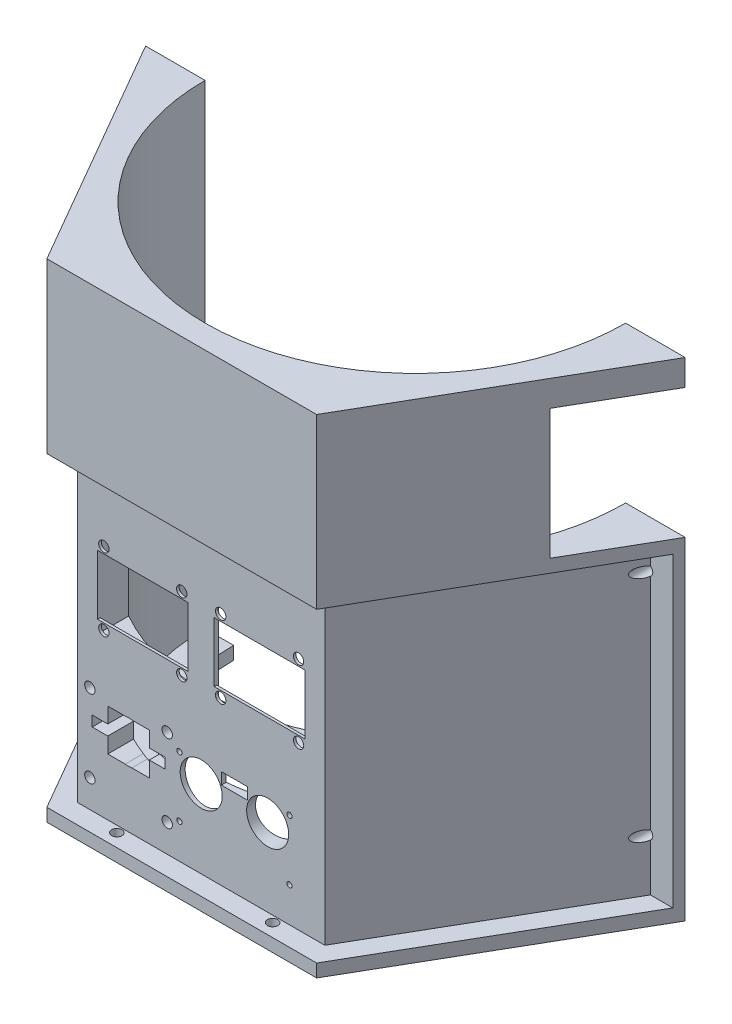
SolidWorks part; units mm, degrees
ref_plane "Front Plane" through (0, 0, 0) normal (0, 0, 1) x (1, 0, 0)
ref_plane "Top Plane" through (0, 0, 0) normal (0, 1, 0) x (1, 0, 0)
ref_plane "Right Plane" through (0, 0, 0) normal (1, 0, 0) x (0, 0, -1)
sketch "Sketch1" plane through (0, 0, 0) normal (0, 1, 0) x (1, 0, 0)
  line L0 (-103.923, 0) -> (103.923, 0)
  line L4 (-103.923, 0) -> (-51.9615, -90)
  line L5 (-51.9615, -90) -> (51.9615, -90)
  line L6 (51.9615, -90) -> (103.923, 0)
  line L8 (77.9423, 45) -> (51.9615, 90) [skipped]
  line L9 (51.9615, 90) -> (-51.9615, 90) [skipped]
  line L10 (-77.9423, 45) -> (-103.923, 0) [skipped]
  arc A0 (-70, 0) -> (70, 0) centre (0, 0) ccw
  arc A2 (-90, 0) -> (90, 0) centre (0, 0) ccw construction
  dimension "D1" = 140
  dimension "D2" = 90
extrude "Boss-Extrude2" add sketch "Sketch1" along normal blind 5 contours A0 L0 L4 L5 L6
sketch "Sketch3" plane through (0, 5, 0) normal (0, 1, 0) x (1, 0, 0)
  line L0 (-103.923, 0) -> (-81, 0)
  line L4 (-93.5307, -3) -> (-47.6314, -82.5)
  line L5 (-47.6314, -82.5) -> (47.6314, -82.5)
  line L6 (47.6314, -82.5) -> (93.5307, -3)
  line L7 (81, 0) -> (103.923, 0)
  line L8 (47.6314, 82.5) -> (-47.6314, 82.5) [skipped]
  line L9 (95.2628, 0) -> (71.4471, 41.25) [skipped]
  line L10 (-71.4471, 41.25) -> (-95.2628, 0) [skipped]
  line L11 (102.191, -3) -> (93.5307, -3)
  line L12 (103.923, 0) -> (102.191, -3)
  line L13 (51.9615, -90) -> (103.923, 0) construction
  line L14 (-102.191, -3) -> (-93.5307, -3)
  line L15 (-103.923, 0) -> (-102.191, -3)
  line L16 (-103.923, 0) -> (-51.9615, -90) construction
  arc A0 (-81, 0) -> (81, 0) centre (0, 0) ccw
  arc A1 (-82.5, 0) -> (82.5, 0) centre (0, 0) ccw construction
  dimension "D1" = 162
extrude "Boss-Extrude3" add sketch "Sketch3" along normal blind 118
sketch "Sketch4" plane through (0, 123, 0) normal (0, 1, 0) x (1, 0, 0)
  line L0 (-103.923, 0) -> (-81, 0)
  line L4 (-103.923, 0) -> (-51.9615, -90)
  line L5 (-51.9615, -90) -> (51.9615, -90)
  line L6 (51.9615, -90) -> (103.923, 0)
  line L7 (81, 0) -> (103.923, 0)
  line L8 (51.9615, 90) -> (-51.9615, 90) [skipped]
  line L9 (103.923, 0) -> (77.9423, 45) [skipped]
  line L10 (-77.9423, 45) -> (-103.923, 0) [skipped]
  arc A0 (-81, 0) -> (81, 0) centre (0, 0) ccw
  arc A1 (-90, 0) -> (90, 0) centre (0, 0) ccw construction
  dimension "D1" = 162
  dimension "D2" = 180
extrude "Boss-Extrude4" add sketch "Sketch4" along normal blind 5
sketch "Sketch5" plane through (0, 128, 0) normal (0, 1, 0) x (1, 0, 0)
  line L0 (84.8705, -33) -> (51.9615, -90)
  line L1 (51.9615, -90) -> (-51.9615, -90)
  line L2 (-51.9615, -90) -> (-103.923, 0)
  line L3 (-103.923, 0) -> (-81, 0)
  line L5 (84.8705, -33) -> (73.973, -33)
  arc A0 (-81, 0) -> (73.973, -33) centre (0, 0) ccw
extrude "Boss-Extrude5" add sketch "Sketch5" along normal blind 50
sketch "Sketch6" plane through (0, 178, 0) normal (0, 1, 0) x (1, 0, 0)
  line L0 (-103.923, 0) -> (-51.9615, -90)
  line L1 (-51.9615, -90) -> (51.9615, -90)
  line L2 (51.9615, -90) -> (103.923, 0)
  line L3 (84.8705, -33) -> (103.923, 0) construction
  line L4 (103.923, 0) -> (81, 0)
  line L5 (-81, 0) -> (-103.923, 0)
  arc A0 (-81, 0) -> (81, 0) centre (0, 0) ccw
extrude "Boss-Extrude6" add sketch "Sketch6" along normal blind 10
sketch "Sketch7" plane through (0, 0, 82.5) normal (0, 0, 1) x (1, 0, 0)
  line L0 (0, 123) -> (0, 93)
  line L1 (-47.6314, 123) -> (47.6314, 123) construction
  line L2 (0, 93) -> (5, 93)
  line L3 (0, 93) -> (-5, 93)
  line L4 (5, 93) -> (40, 93)
  line L5 (40, 93) -> (40, 70)
  line L6 (40, 70) -> (5, 70)
  line L7 (-5, 93) -> (-40, 93)
  line L8 (-40, 93) -> (-40, 70)
  line L9 (-40, 70) -> (-5, 70)
  line L10 (-5, 93) -> (-5, 70)
  line L11 (5, 93) -> (5, 70)
  dimension "D1" = 30
  dimension "D2" = 5
  dimension "D3" = 5
  dimension "D4" = 35
  dimension "D5" = 23
  dimension "D6" = 35
  dimension "D7" = 35
  dimension "D8" = 35
  dimension "D9" = 23
extrude "Cut-Extrude1" cut sketch "Sketch7" against normal blind 1 contours L10 L7 L8 L9 | L4 L11 L6 L5
sketch "Sketch8" plane through (0, 0, 81.5) normal (0, 0, 1) x (1, 0, 0)
  line L0 (-40, 93) -> (-40, 98)
  line L1 (-40, 70) -> (-40, 65)
  line L2 (-40, 98) -> (-5, 98)
  line L3 (-5, 98) -> (-5, 65)
  line L4 (-5, 65) -> (-40, 65)
  line L5 (-40, 70) -> (-40, 93)
  line L6 (5, 93) -> (40, 93) construction
  line L7 (5, 70) -> (5, 98)
  line L8 (5, 98) -> (40.0427, 98)
  line L9 (40.0427, 98) -> (40.0427, 65)
  line L10 (40.0427, 65) -> (5, 65)
  line L11 (5, 65) -> (5, 70)
  dimension "D1" = 5
  dimension "D2" = 5
  dimension "D3" = 5
extrude "Cut-Extrude2" cut sketch "Sketch8" against normal blind 50
sketch "Sketch9" plane through (0, 0, 82.5) normal (0, 0, 1) x (1, 0, 0)
  line L0 (-47.6314, 5) -> (47.6314, 5) construction
  circle A0 centre (0, 35) radius 8.1
  circle A1 centre (25.6, 35) radius 8.1
  circle A2 centre (-28, 35) radius 8.1
  dimension "D2" = 16.2
  dimension "D3" = 25.6
  dimension "D4" = 16.2
  dimension "D5" = 16.2
  dimension "D6" = 28
  dimension "D1" = 30
extrude "Cut-Extrude3" cut sketch "Sketch9" against normal blind 10
sketch "Sketch10" plane through (0, 0, 0) normal (0, 0, -1) x (-1, 0, 0)
  line L0 (-92.4615, 128) -> (-92.4615, 113)
  line L1 (-103.923, 128) -> (-81, 128) construction
  line L2 (-92.4615, 25) -> (-92.4615, 0)
  line L3 (-70, 0) -> (-103.923, 0) construction
  line L4 (92.4615, 188) -> (92.4615, 113)
  line L5 (81, 188) -> (103.923, 188) construction
  line L7 (92.4615, 25) -> (92.4615, 0)
  line L8 (103.923, 0) -> (70, 0) construction
  circle A0 centre (92.4615, 113) radius 2
  circle A1 centre (-92.4615, 113) radius 2
  circle A2 centre (-92.4615, 25) radius 2
  circle A3 centre (92.4615, 25) radius 2
  dimension "D5" = 4
  dimension "D6" = 4
  dimension "D7" = 4
  dimension "D8" = 4
  dimension "D1" = 15
  dimension "D2" = 25
  dimension "D3" = 25
  dimension "D4" = 75
extrude "Cut-Extrude4" cut sketch "Sketch10" against normal blind 10
sketch "Sketch11" plane through (0, 0, 0) normal (0, -1, 0) x (1, 0, 0)
  line L0 (0, 90) -> (0, 85)
  line L1 (-51.9615, 90) -> (51.9615, 90) construction
  line L2 (0, 85) -> (30, 85)
  line L3 (0, 85) -> (-30, 85)
  circle A0 centre (-30, 85) radius 2
  circle A1 centre (30, 85) radius 2
  dimension "D4" = 4
  dimension "D5" = 4
  dimension "D1" = 5
  dimension "D2" = 30
  dimension "D3" = 30
extrude "Cut-Extrude5" cut sketch "Sketch11" against normal blind 10
sketch "Sketch12" plane through (0, 0, 82.5) normal (0, 0, 1) x (1, 0, 0)
  line L0 (-40, 93) -> (-40, 95.5)
  line L1 (-40, 95.5) -> (-37.5, 95.5)
  line L2 (-5, 93) -> (-5, 95.5)
  line L3 (-5, 95.5) -> (-7.5, 95.5)
  line L4 (-40, 70) -> (-40, 67.5)
  line L5 (-40, 67.5) -> (-37.5, 67.5)
  line L6 (-5, 70) -> (-5, 67.5)
  line L7 (-5, 67.5) -> (-7.5, 67.5)
  line L8 (0, 0) -> (0, 88.9926) construction
  circle A0 centre (-37.5, 95.5) radius 2
  circle A1 centre (-7.5, 95.5) radius 2
  circle A2 centre (-7.5, 67.5) radius 2
  circle A3 centre (-37.5, 67.5) radius 2
  circle A4 centre (7.5, 67.5) radius 2
  circle A5 centre (37.5, 67.5) radius 2
  circle A6 centre (7.5, 95.5) radius 2
  circle A7 centre (37.5, 95.5) radius 2
  dimension "D9" = 4
  dimension "D10" = 4
  dimension "D11" = 4
  dimension "D12" = 4
  dimension "D1" = 2.5
  dimension "D2" = 2.5
  dimension "D3" = 2.5
  dimension "D4" = 2.5
  dimension "D5" = 2.5
  dimension "D6" = 2.5
  dimension "D7" = 2.5
  dimension "D8" = 2.5
extrude "Cut-Extrude6" cut sketch "Sketch12" against normal blind 10
sketch "Sketch13" plane through (0, 0, 82.5) normal (0, 0, 1) x (1, 0, 0)
  line L1 (12.8, 38.5) -> (17.85, 38.5)
  line L2 (12.8, 43) -> (35.4, 43)
  line L3 (35.4, 43) -> (35.4, 17)
  line L4 (35.4, 17) -> (-9.8, 17)
  line L5 (-9.8, 17) -> (-9.8, 43)
  line L6 (-9.8, 43) -> (12.8, 43)
  line L7 (12.8, 38.5) -> (7.75, 38.5)
  line L8 (7.75, 38.5) -> (7.75, 43)
  line L9 (17.85, 38.5) -> (17.85, 43)
  circle A0 centre (34, 41.6) radius 1
  circle A1 centre (-8.4, 41.6) radius 1
  circle A2 centre (-8.4, 18.4) radius 1
  circle A3 centre (34, 18.4) radius 1
  point P0 (-8.4, 43)
  point P1 (-9.8, 41.6)
  point P4 (34, 43)
  point P9 (35.4, 41.6)
  dimension "D9" = 2
  dimension "D10" = 2
  dimension "D11" = 2
  dimension "D12" = 2
  dimension "D13" = 1.4
  dimension "D14" = 1.4
  dimension "D15" = 1.4
  dimension "D16" = 1.4
  dimension "D1" = 26
  dimension "D2" = 1.4
  dimension "D3" = 45.2
  dimension "D4" = 22.6
  dimension "D5" = 26
  dimension "D6" = 1.4
  dimension "D7" = 1.4
  dimension "D8" = 1.4
  dimension "D17" = 4.5
  dimension "D18" = 5.05
  dimension "D19" = 5.05
extrude "Cut-Extrude7" cut sketch "Sketch13" against normal blind 10 contours A1 | L1 L9 L2 L6 L8 L7 | A2 | A3 | A0
sketch "Sketch14" plane through (0, 0, 82.5) normal (0, 0, 1) x (1, 0, 0)
  line L0 (-28, 35) -> (-28, 48)
  line L1 (-28, 48) -> (-10.5, 48)
  line L2 (-10.5, 48) -> (-10.5, 8)
  line L3 (-10.5, 8) -> (-45.5, 8)
  line L4 (-45.5, 8) -> (-45.5, 48)
  line L5 (-45.5, 48) -> (-28, 48)
  circle A0 centre (-13.1, 45.7) radius 2
  circle A1 centre (-42.9, 45.7) radius 2
  circle A2 centre (-42.9, 15.7) radius 2
  circle A3 centre (-13.1, 15.7) radius 2
  circle M14 centre (-8.4, 41.6) radius 1
  dimension "D6" = 2.3
  dimension "D7" = 2.6
  dimension "D8" = 2.3
  dimension "D9" = 2.6
  dimension "D10" = 2.6
  dimension "D11" = 2.6
  dimension "D12" = 30
  dimension "D13" = 30
  dimension "D14" = 4
  dimension "D15" = 4
  dimension "D16" = 4
  dimension "D17" = 4
  dimension "D1" = 13
  dimension "D2" = 17.5
  dimension "D3" = 40
  dimension "D4" = 35
  dimension "D5" = 40
extrude "Cut-Extrude10" cut sketch "Sketch14" against normal blind 83 contours A0 M14 | A3 | A2 | A1
sketch "Sketch15" plane through (0, 0, 82.5) normal (0, 0, 1) x (1, 0, 0)
  line L2 (-14, 35) -> (-14, 37)
  line L3 (-14, 35) -> (-14, 33)
  line L4 (-42, 35) -> (-42, 37)
  line L5 (-42, 35) -> (-42, 33)
  line L7 (-28, 43) -> (-20, 43)
  line L8 (-28, 43) -> (-36, 43)
  line L10 (-36, 43) -> (-36, 37)
  line L11 (-36, 27) -> (-20, 27)
  line L12 (-20, 27) -> (-20, 33)
  line L13 (-14, 37) -> (-20, 37)
  line L14 (-14, 33) -> (-20, 33)
  line L15 (-42, 37) -> (-36, 37)
  line L16 (-42, 33) -> (-36, 33)
  line L17 (-36, 33) -> (-36, 27)
  line L18 (-20, 37) -> (-20, 43)
  dimension "D3" = 2
  dimension "D4" = 2
  dimension "D5" = 2
  dimension "D6" = 2
  dimension "D7" = 8
  dimension "D8" = 8
extrude "Cut-Extrude11" cut sketch "Sketch15" against normal blind 83
